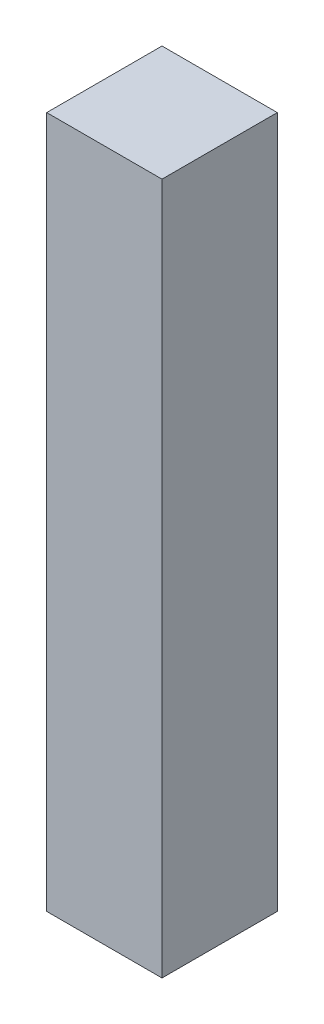
SolidWorks part; units mm, degrees
ref_plane "Front Plane" through (0, 0, 0) normal (0, 0, 1) x (1, 0, 0)
ref_plane "Top Plane" through (0, 0, 0) normal (0, 1, 0) x (1, 0, 0)
ref_plane "Right Plane" through (0, 0, 0) normal (1, 0, 0) x (0, 0, -1)
sketch "Sketch1" plane through (0, 0, 0) normal (0, 1, 0) x (1, 0, 0)
  line L1 (6.35, -6.35) -> (-6.35, -6.35)
  line L2 (6.35, -6.35) -> (6.35, 6.35)
  line L3 (6.35, 6.35) -> (-6.35, 6.35)
  line L4 (-6.35, -6.35) -> (-6.35, 6.35)
  line L5 (6.35, -6.35) -> (-6.35, 6.35) construction
  line L6 (6.35, 6.35) -> (-6.35, -6.35) construction
  point P0 (0, 0)
  dimension "D1" = 12.7
  dimension "D2" = 12.7
extrude "Boss-Extrude1" add sketch "Sketch1" along normal blind 76.2
sketch "Sketch2" plane through (0, 0, 6.35) normal (0, 0, 1) x (1, 0, 0)
  text T0 "<-----------3 INCHES------------------->"
